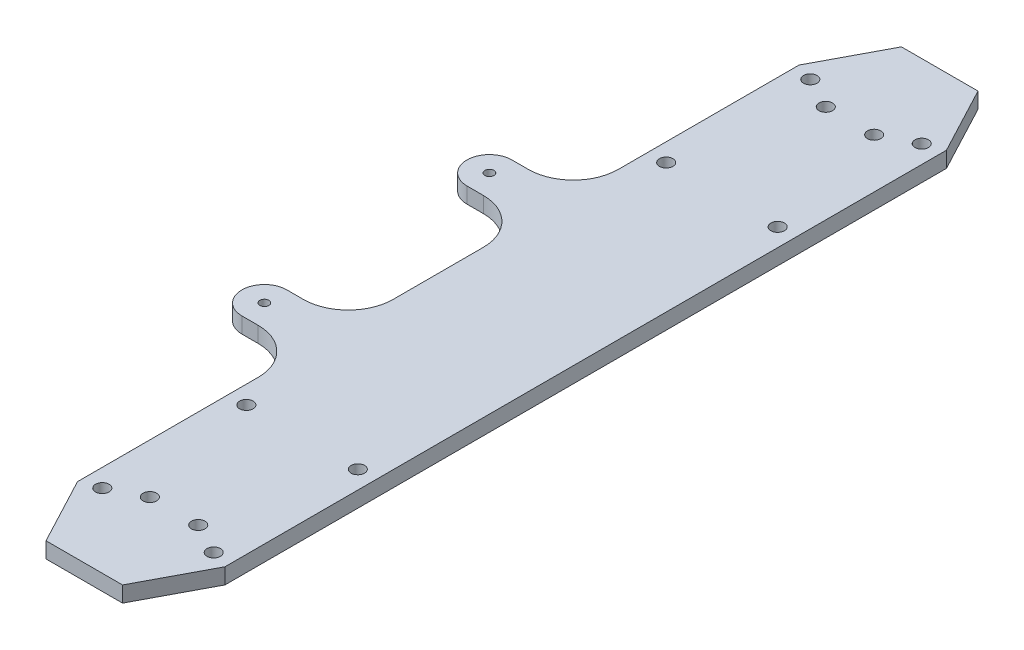
SolidWorks part; units mm, degrees
material "Thornel Mat VMA"
ref_plane "Front Plane" through (0, 0, 0) normal (0, 0, 1) x (1, 0, 0)
ref_plane "Top Plane" through (0, 0, 0) normal (0, 1, 0) x (1, 0, 0)
ref_plane "Right Plane" through (0, 0, 0) normal (1, 0, 0) x (0, 0, -1)
sketch "Sketch1" plane through (0, 0, 0) normal (0, 1, 0) x (1, 0, 0)
  line L0 (-16.375, -95) -> (16.375, -95)
  line L1 (-16.375, -95) -> (-16.375, 95)
  line L2 (16.375, -95) -> (16.375, 95)
  line L3 (-16.375, 95) -> (16.375, 95)
  line L4 (-16.375, -95) -> (16.375, 95) construction
  line L5 (16.375, -95) -> (-16.375, 95) construction
  point P1 (0, 0)
  dimension "D1" = 32.75
  dimension "D2" = 190
extrude "Boss-Extrude1" add sketch "Sketch1" along normal blind 3.5
sketch "Sketch3" plane through (0, 3.5, 0) normal (0, 1, 0) x (1, 0, 0)
  line L0 (0, 0) -> (0, -56.25)
  line L1 (0, -56.25) -> (0, -72.875)
  line L2 (0, -72.875) -> (0, -78.625)
  line L3 (0, -78.625) -> (-16.375, -78.625)
  line L4 (-16.375, 95) -> (-16.375, -95) construction
  line L5 (-16.375, -78.625) -> (-16.375, -80.125)
  line L9 (0, -78.625) -> (0, -95)
  line L10 (-16.375, -95) -> (16.375, -95) construction
  line L11 (0, -95) -> (-8.5, -95)
  line L12 (-16.375, -80.125) -> (-8.5, -95)
  line L13 (-16.375, -95) -> (-16.375, -80.125)
  line L14 (-16.375, -78.625) -> (-16.375, -46.625)
  line L15 (-16.375, -46.625) -> (-12.375, -46.625)
  circle A0 centre (-12.375, -78.625) radius 1.5
  circle A1 centre (-12.375, -46.625) radius 1.5
  dimension "D7" = 3
  dimension "D9" = 3
  dimension "D8" = 4
  dimension "D1" = 56.25
  dimension "D2" = 16.625
  dimension "D3" = 5.75
  dimension "D4" = 1.5
  dimension "D5" = 8.5
  dimension "D6" = 32
extrude "Cut-Extrude1" cut sketch "Sketch3" against normal through all
mirror "Mirror1" about plane through (0, 0, 0) normal (1, 0, 0) of "Cut-Extrude1"
mirror "Mirror2" about plane through (0, 0, 0) normal (0, 0, 1) of "Mirror1", "Cut-Extrude1"
sketch "Sketch4" plane through (0, 3.5, 0) normal (0, 1, 0) x (1, 0, 0)
  line L0 (12.375, -78.625) -> (5.375, -78.625)
  line L1 (5.375, -78.625) -> (5.375, -75.065)
  circle A0 centre (5.375, -75.065) radius 1.5
  dimension "D3" = 3
  dimension "D1" = 7
  dimension "D2" = 3.56
extrude "Cut-Extrude2" cut sketch "Sketch4" against normal through all
mirror "Mirror3" about plane through (0, 0, 0) normal (1, 0, 0) of "Cut-Extrude2"
mirror "Mirror4" about plane through (0, 0, 0) normal (0, 0, 1) of "Mirror3", "Cut-Extrude2"
sketch "Sketch5" plane through (0, 0, 0) normal (0, -1, 0) x (1, 0, 0)
  line L0 (12.375, 46.625) -> (12.375, 24.995)
  line L1 (12.375, 24.995) -> (30.005, 24.995)
  line L2 (17.375, 46.625) -> (17.375, 29.995)
  line L3 (17.375, 29.995) -> (30.005, 29.995)
  line L4 (7.375, 46.625) -> (7.375, 19.995)
  line L5 (7.375, 19.995) -> (30.005, 19.995)
  line L6 (17.375, 29.995) -> (12.375, 29.995)
  circle A0 centre (30.005, 24.995) radius 1
  arc A1 (30.005, 29.995) -> (30.005, 19.995) centre (30.005, 24.995) cw
  dimension "D3" = 2
  dimension "D1" = 21.63
  dimension "D2" = 17.63
  dimension "D4" = 5
  dimension "D5" = 5
extrude "Boss-Extrude2" add sketch "Sketch5" against normal up to surface (3.5 mm away)
fillet "Fillet1" radius 10 1 edges at (16.375, 1.75, 29.995)
fillet "Fillet2" radius 10 1 edges at (16.375, 1.75, 19.995)
mirror "Mirror13" about plane through (0, 0, 0) normal (1, 0, 0) of "Boss-Extrude2"
fillet "Fillet5" radius 10 1 edges at (-16.375, 1.75, 29.995)
fillet "Fillet6" radius 10 1 edges at (-16.375, 1.75, 19.995)
mirror "Mirror14" about plane through (0, 0, 0) normal (0, 0, 1) of "Mirror13", "Boss-Extrude2"
fillet "Fillet7" radius 10 1 edges at (-16.375, 1.75, -29.995)
fillet "Fillet8" radius 10 1 edges at (-16.375, 1.75, -19.995)
sketch "Sketch6" plane through (0, 3.5, 0) normal (0, 1, 0) x (1, 0, 0)
  line L0 (16.375, 5) -> (16.375, 44.9248)
  line L1 (16.375, -9.995) -> (16.375, 19.995) construction
  line L2 (16.375, 29.995) -> (16.375, 80.125) construction
  line L3 (16.375, 44.9248) -> (47.7165, 44.9248)
  line L4 (47.7165, 44.9248) -> (47.7165, -55.8942)
  line L5 (47.7165, -55.8942) -> (16.375, -55.8942)
  line L6 (16.375, -80.125) -> (16.375, -39.995) construction
  line L7 (16.375, -55.8942) -> (16.375, 5)
extrude "Cut-Extrude3" cut sketch "Sketch6" against normal through all
